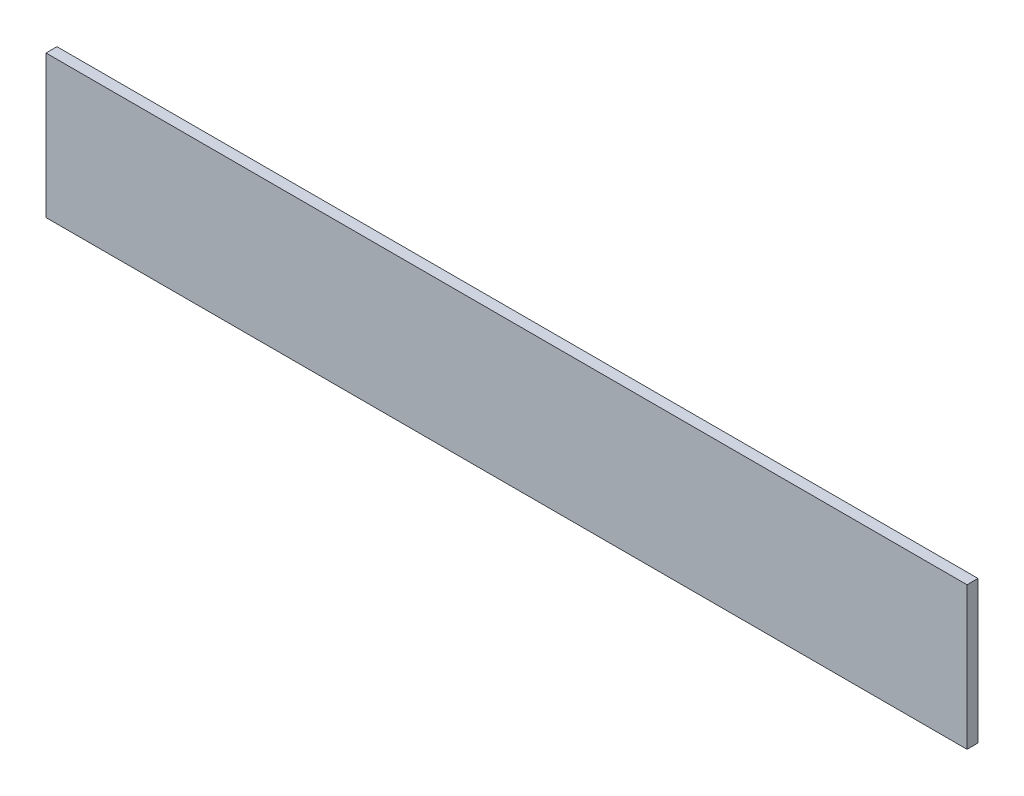
SolidWorks part; units mm, degrees
ref_plane "Front Plane" through (0, 0, 0) normal (0, 0, 1) x (1, 0, 0)
ref_plane "Top Plane" through (0, 0, 0) normal (0, 1, 0) x (1, 0, 0)
ref_plane "Right Plane" through (0, 0, 0) normal (1, 0, 0) x (0, 0, -1)
sketch "Sketch1" plane through (0, 0, 0) normal (0, 0, 1) x (1, 0, 0)
  line L1 (0, 0) -> (420, 0)
  line L2 (0, 0) -> (0, -65)
  line L3 (0, -65) -> (420, -65)
  line L4 (420, 0) -> (420, -65)
  dimension "D1" = 420
  dimension "D2" = 65
extrude "Boss-Extrude1" add sketch "Sketch1" along normal blind 5
